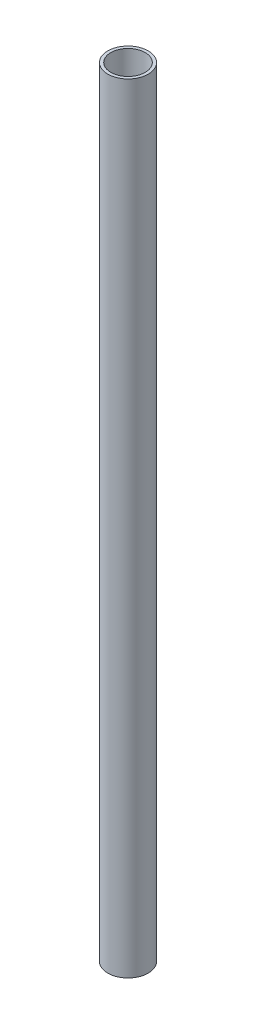
SolidWorks part; units mm, degrees
material "Copper"
ref_plane "Front Plane" through (0, 0, 0) normal (0, 0, 1) x (1, 0, 0)
ref_plane "Top Plane" through (0, 0, 0) normal (0, 1, 0) x (1, 0, 0)
ref_plane "Right Plane" through (0, 0, 0) normal (1, 0, 0) x (0, 0, -1)
sketch "Sketch1" plane through (0, 0, 0) normal (0, 0, 1) x (1, 0, 0)
  line L0 (0, -69.1907) -> (0, 69.1907) construction
  line L1 (0, 0) -> (111.878, 0) construction
  line L2 (9.4615, -214.249) -> (11.1125, -214.249)
  line L3 (9.4615, -214.249) -> (9.4615, 214.249)
  line L4 (9.4615, 214.249) -> (11.1125, 214.249)
  line L5 (11.1125, -214.249) -> (11.1125, 214.249)
  line L6 (9.4615, -214.249) -> (11.1125, 214.249) construction
  line L7 (9.4615, 214.249) -> (11.1125, -214.249) construction
  point P0 (10.287, 0)
  point P4 (0, 0)
  dimension "D1" = 11.1125
  dimension "D2" = 1.651
  dimension "L" = 428.498
revolve "Revolve1" add sketch "Sketch1" angle 360 about L0
ref_plane "Plane1" through (11.1125, 0, 0) normal (1, 0, 0) x (0, 0, -1)
hole_wizard "#4 Clearance Hole1" [suppressed] positions "Sketch2" profile "Sketch3" hole size "#4" standard "ANSI Inch"
sketch "Sketch2" plane through (11.1125, 0, 0) normal (1, 0, 0) x (0, 0, -1)
  line L0 (9.4615, 185.547) -> (-9.4615, 185.547) construction
  line L1 (0, 185.547) -> (0, -185.547) construction
  line L2 (11.1125, 185.547) -> (-11.1125, 185.547) construction
  line L3 (-11.1125, -185.547) -> (11.1125, -185.547) construction
  point P0 (0, 107.6173)
  point P2 (0, -107.6173)
  dimension "D1" = 89.9846
  dimension "D2" = 338.5134
sketch "Sketch3" plane through (11.1125, 107.6173, 0) normal (0, 1, 0) x (0, 0, -1)
  line L0 (0, 0) -> (0, 22.225)
  line L1 (0, 22.225) -> (1.6319, 22.225)
  line L2 (1.6319, 22.225) -> (1.6319, 0)
  line L5 (1.6319, 0) -> (0, 0)
  line L11 (0, -6.35) -> (0, 107.95) construction
  dimension "Thru Hole Dia." = 3.2639
  dimension "Thru Hole Depth" = 22.225
ref_plane "Plane2" [suppressed] through (0, 0, 0) normal (0, -1, 0) x (-1, 0, 0)
equation "\"h1\"= .21in"
equation "\"h2\"= .79in"
equation "\"D1@Sketch2\"=\"L\"*\"h1\""
equation "\"D2@Sketch2\"=\"L\"*\"h2\""
